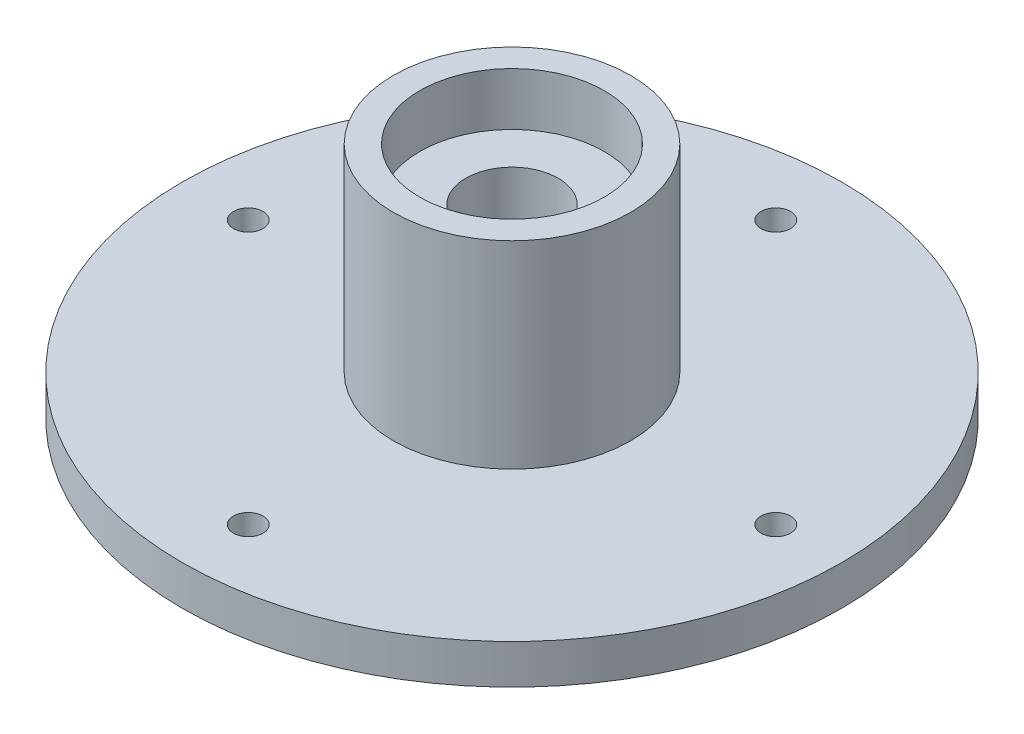
SolidWorks part; units mm, degrees
ref_plane "Front Plane" through (0, 0, 0) normal (0, 0, 1) x (1, 0, 0)
ref_plane "Top Plane" through (0, 0, 0) normal (0, 1, 0) x (1, 0, 0)
ref_plane "Right Plane" through (0, 0, 0) normal (1, 0, 0) x (0, 0, -1)
sketch "Sketch2" plane through (0, 0, 0) normal (0, 1, 0) x (1, 0, 0)
  circle A0 centre (0, 0) radius 50
  dimension "D1" = 100
extrude "Boss-Extrude1" add sketch "Sketch2" along normal blind 6
sketch "Sketch3" plane through (0, 6, 0) normal (0, 1, 0) x (1, 0, 0)
  circle A0 centre (0, 0) radius 18
  dimension "D1" = 36
extrude "Boss-Extrude2" add sketch "Sketch3" along normal blind 30
sketch "Sketch4" plane through (0, 36, 0) normal (0, 1, 0) x (1, 0, 0)
  circle A0 centre (0, 0) radius 7
  dimension "D1" = 14
extrude "Cut-Extrude1" cut sketch "Sketch4" against normal through all
sketch "Sketch5" plane through (0, 36, 0) normal (0, 1, 0) x (1, 0, 0)
  circle A0 centre (0, 0) radius 14
  dimension "D1" = 28
extrude "Cut-Extrude2" cut sketch "Sketch5" against normal blind 8
sketch "Sketch6" plane through (0, 0, 0) normal (0, -1, 0) x (1, 0, 0)
  circle A0 centre (0, 0) radius 14
  dimension "D1" = 28
extrude "Cut-Extrude3" cut sketch "Sketch6" against normal blind 8
sketch "Sketch7" plane through (0, 0, 0) normal (0, -1, 0) x (1, 0, 0)
  line L0 (0, 0) -> (50, 0) construction
  circle A1 centre (40, 0) radius 2.25
  circle A2 centre (0, 0) radius 50 construction
  dimension "D1" = 4.5
  dimension "D2" = 40
extrude "Cut-Extrude4" cut sketch "Sketch7" against normal through all
pattern_circular "CirPattern1" count 4 over 360 about axis through (0, 0, 0) along (0, 1, 0) of "Cut-Extrude4"
